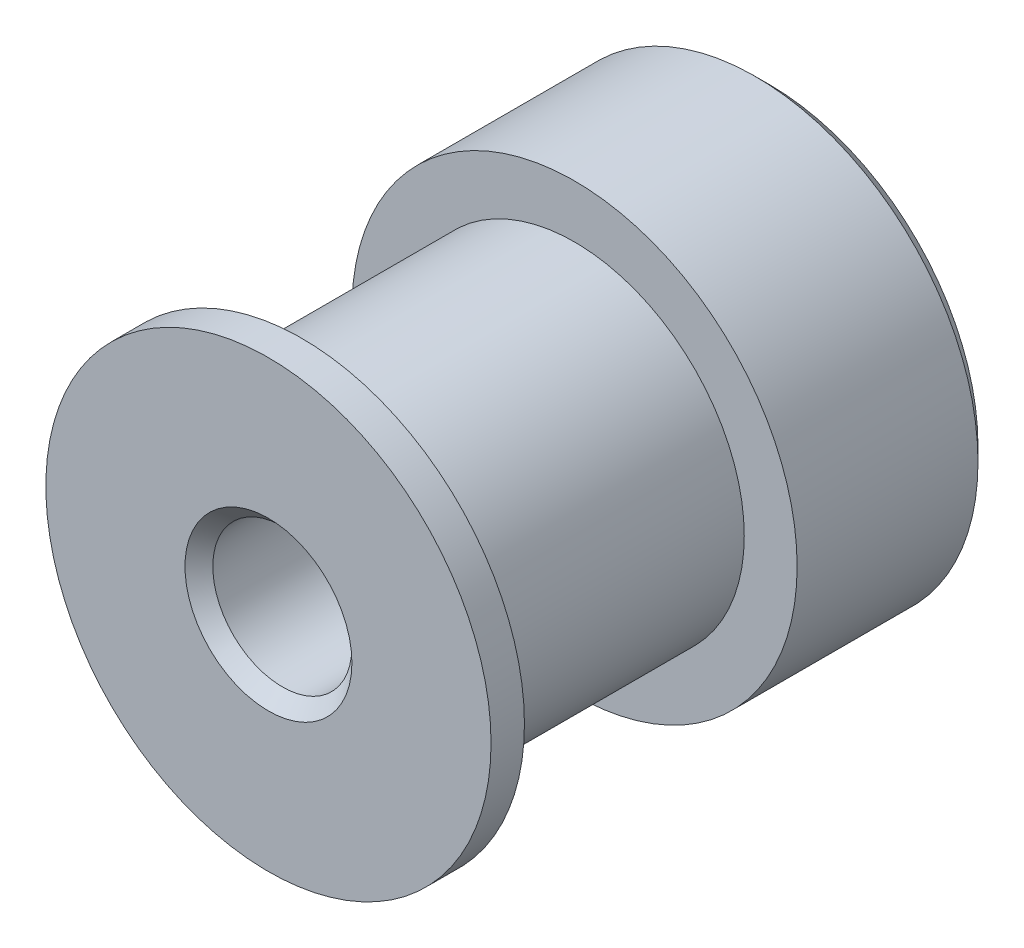
SolidWorks part; units mm, degrees
ref_plane "Alzado" through (0, 0, 0) normal (0, 0, 1) x (1, 0, 0)
ref_plane "Planta" through (0, 0, 0) normal (0, 1, 0) x (1, 0, 0)
ref_plane "Vista lateral" through (0, 0, 0) normal (1, 0, 0) x (0, 0, -1)
sketch "Croquis1" plane through (0, 0, 0) normal (0, 0, 1) x (1, 0, 0)
  circle A0 centre (0, 0) radius 8
  dimension "D1" = 16
extrude "Saliente-Extruir1" add sketch "Croquis1" along normal blind 7
sketch "Croquis2" plane through (0, 0, 7) normal (0, 0, 1) x (1, 0, 0)
  circle A0 centre (0, 0) radius 6.1
  dimension "D1" = 12.2
extrude "Saliente-Extruir2" add sketch "Croquis2" along normal blind 9.8
sketch "Croquis3" plane through (0, 0, 16.8) normal (0, 0, 1) x (1, 0, 0)
  circle A0 centre (0, 0) radius 8
  dimension "D1" = 16
extrude "Saliente-Extruir3" add sketch "Croquis3" along normal blind 1.2
sketch "Croquis4" plane through (0, 0, 18) normal (0, 0, 1) x (1, 0, 0)
  circle A0 centre (0, 0) radius 2.5
  dimension "D1" = 5
extrude "Cortar-Extruir1" cut sketch "Croquis4" against normal through all
chamfer "Chaflán1" distance 0.5 angle 45 3 edges at (8, 0, 0) (2.5, 0, 0) (2.5, 0, 18)
sketch "Croquis5" plane through (0, 0, 0) normal (1, 0, 0) x (0, 0, -1)
  line L0 (0, 0) -> (-3.5, 0) construction
  circle A0 centre (-3.5, 0) radius 1.5
  dimension "D2" = 3
  dimension "D1" = 3.5
extrude "Cortar-Extruir2" cut sketch "Croquis5" against normal through all
sketch "Croquis6" plane through (0, 0, 0) normal (0, 1, 0) x (1, 0, 0)
  line L0 (0, 0) -> (0, -3.5) construction
  circle A0 centre (0, -3.5) radius 1.5
  dimension "D2" = 3
  dimension "D1" = 3.5
extrude "Cortar-Extruir3" cut sketch "Croquis6" against normal through all
